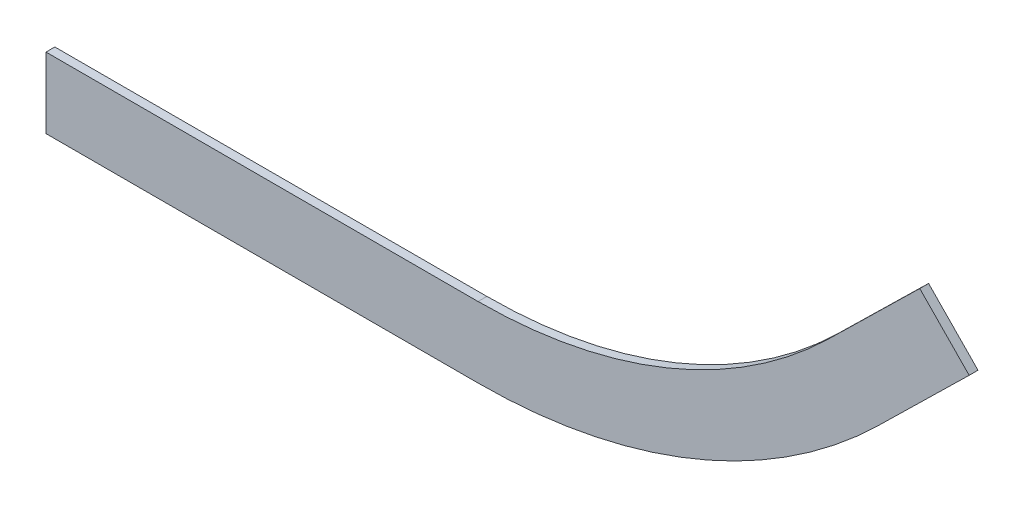
SolidWorks part; units mm, degrees
other "Папка сварных швов"
material "Ст 3 ГОСТ 380-88"
ref_plane "Front" through (0, 0, 0) normal (0, 0, 1) x (1, 0, 0)
ref_plane "Top" through (0, 0, 0) normal (0, 1, 0) x (1, 0, 0)
ref_plane "Right" through (0, 0, 0) normal (1, 0, 0) x (0, 0, -1)
sketch "Sketch4" plane through (0, 0, 0) normal (0, 0, 1) x (1, 0, 0)
  line B0 (50, 40) -> (244.6554, 40)
  line B1 (443.3207, 121.0515) -> (459.0665, 136.465)
  line B2 (471.3054, 92.4708) -> (487.0475, 107.8807)
  line B3 (50, 0) -> (244.6502, 0)
  line B4 (0, 40) -> (50, 40)
  line B5 (459.0665, 136.465) -> (494.7969, 171.4413)
  line B6 (0, 0) -> (50, 0)
  line B7 (487.0475, 107.8807) -> (522.7779, 142.857)
  line B8 (494.7969, 171.4413) -> (522.7779, 142.857)
  line B9 (0, 40) -> (0, 0)
  arc B10 (244.6502, 0) -> (471.3054, 92.4708) centre (244.6502, 324.0128) ccw
  arc B11 (244.6554, 40) -> (443.3207, 121.0515) centre (244.6554, 324) ccw
  line B12 (0, 0) -> (522.7779, 0) construction
sketch_block_instance "дуга малирования-1"
sketch_block "Block2" parameters "D1"=522.7779
extrude "Boss-Extrude1" add sketch "Sketch4" against normal mid plane 5
